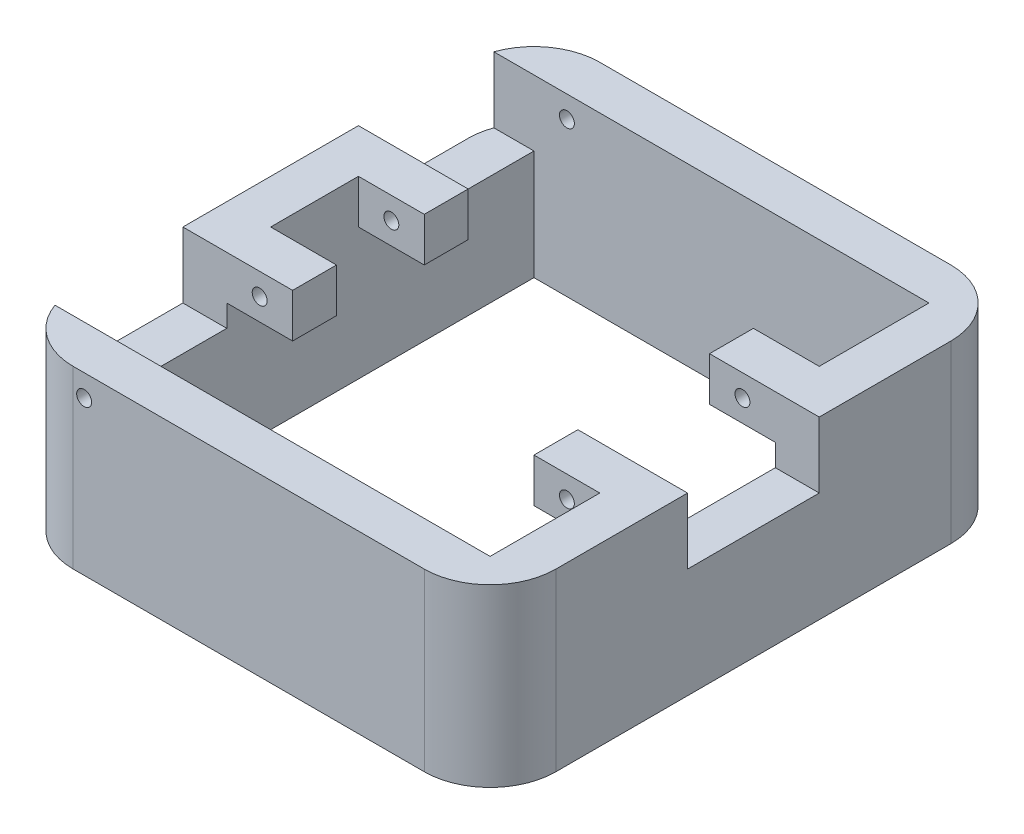
SolidWorks part; units mm, degrees
ref_plane "Front Plane" through (0, 0, 0) normal (0, 0, 1) x (1, 0, 0)
ref_plane "Top Plane" through (0, 0, 0) normal (0, 1, 0) x (1, 0, 0)
ref_plane "Right Plane" through (0, 0, 0) normal (1, 0, 0) x (0, 0, -1)
sketch "Sketch1" plane through (0, 0, 0) normal (0, 1, 0) x (1, 0, 0)
  line L1 (-45.2841, 33.3096) -> (34.7159, 33.3096)
  line L2 (-60.2841, 18.3096) -> (-60.2841, -71.6904)
  line L3 (-45.2841, -86.6904) -> (34.7159, -86.6904)
  line L4 (49.7159, 18.3096) -> (49.7159, -71.6904)
  line L5 (-50.2841, 23.3096) -> (39.7159, 23.3096)
  line L6 (-50.2841, 23.3096) -> (-50.2841, -76.6904)
  line L7 (-50.2841, -76.6904) -> (39.7159, -76.6904)
  line L8 (39.7159, 23.3096) -> (39.7159, -76.6904)
  arc A0 (-45.2841, 33.3096) -> (-60.2841, 18.3096) centre (-45.2841, 18.3096) ccw
  arc A1 (-60.2841, -71.6904) -> (-45.2841, -86.6904) centre (-45.2841, -71.6904) ccw
  arc A2 (34.7159, -86.6904) -> (49.7159, -71.6904) centre (34.7159, -71.6904) ccw
  arc A3 (49.7159, 18.3096) -> (34.7159, 33.3096) centre (34.7159, 18.3096) ccw
  dimension "D3" = 15
  dimension "D4" = 15
  dimension "D5" = 15
  dimension "D1" = 120
  dimension "D2" = 110
  dimension "D6" = 100
  dimension "D7" = 90
  dimension "D8" = 10
  dimension "D9" = 10
extrude "Boss-Extrude1" add sketch "Sketch1" along normal blind 40
sketch "Sketch3" plane through (0, 40, 0) normal (0, 1, 0) x (1, 0, 0)
  line L0 (-60.2841, -6.6904) -> (-35.2841, -6.6904)
  line L1 (-60.2841, 18.3096) -> (-60.2841, -71.6904) construction
  line L2 (-35.2841, -6.6904) -> (-35.2841, -46.6904)
  line L3 (-35.2841, -46.6904) -> (-60.2841, -46.6904)
  line L4 (-60.2841, -46.6904) -> (-60.2841, -6.6904)
  line L5 (39.7159, 23.3096) -> (-50.2841, 23.3096) construction
  line L6 (-50.2841, 23.3096) -> (-50.2841, -76.6904) construction
  dimension "D1" = 40
  dimension "D2" = 30
  dimension "D3" = 15
extrude "Boss-Extrude3" add sketch "Sketch3" against normal blind 10
sketch "Sketch5" plane through (0, 40, 0) normal (0, 1, 0) x (1, 0, 0)
  line L0 (-35.2841, -46.6904) -> (-35.2841, -6.6904) construction
  line L1 (-35.2841, -36.6904) -> (-50.2841, -36.6904)
  line L2 (-35.2841, -36.6904) -> (-35.2841, -16.6904)
  line L3 (-35.2841, -16.6904) -> (-50.2841, -16.6904)
  line L4 (-50.2841, -36.6904) -> (-50.2841, -16.6904)
  line L5 (-60.2841, 18.3096) -> (-60.2841, -71.6904) construction
  line L6 (-50.2841, -46.6904) -> (-35.2841, -46.6904) construction
  line L7 (-35.2841, -6.6904) -> (-50.2841, -6.6904) construction
  dimension "D1" = 10
  dimension "D2" = 10
  dimension "D3" = 10
extrude "Cut-Extrude1" cut sketch "Sketch5" against normal blind 10
sketch "Sketch6" plane through (0, 40, 0) normal (0, 1, 0) x (1, 0, 0)
  line L0 (49.7159, -71.6904) -> (49.7159, 18.3096) construction
  line L1 (49.7159, -51.6904) -> (24.7159, -51.6904)
  line L2 (49.7159, -51.6904) -> (49.7159, -41.6904)
  line L3 (49.7159, -41.6904) -> (24.7159, -41.6904)
  line L4 (24.7159, -51.6904) -> (24.7159, -41.6904)
  line L5 (-50.2841, -76.6904) -> (39.7159, -76.6904) construction
  line L6 (39.7159, -76.6904) -> (39.7159, 23.3096) construction
  line L7 (39.7159, 23.3096) -> (-50.2841, 23.3096) construction
  line L8 (49.7159, -1.6904) -> (24.7159, -1.6904)
  line L9 (49.7159, -1.6904) -> (49.7159, -11.6904)
  line L10 (49.7159, -11.6904) -> (24.7159, -11.6904)
  line L11 (24.7159, -1.6904) -> (24.7159, -11.6904)
  dimension "D1" = 10
  dimension "D2" = 25
  dimension "D3" = 15
  dimension "D4" = 10
  dimension "D5" = 25
extrude "Boss-Extrude4" add sketch "Sketch6" against normal blind 10
sketch "Sketch7" plane through (0, 40, 0) normal (0, 1, 0) x (1, 0, 0)
  line L0 (-60.2841, 18.3096) -> (-60.2841, -71.6904) construction
  line L1 (-50.2841, 23.3096) -> (-60.2841, 23.3096)
  line L2 (-50.2841, 23.3096) -> (-50.2841, -6.6904)
  line L3 (-50.2841, -6.6904) -> (-60.2841, -6.6904)
  line L4 (-60.2841, 23.3096) -> (-60.2841, -6.6904)
  line L5 (-35.2841, -6.6904) -> (-50.2841, -6.6904) construction
  line L6 (-50.2841, -46.6904) -> (-35.2841, -46.6904) construction
  line L7 (-50.2841, -76.6904) -> (-60.2841, -76.6904)
  line L8 (-50.2841, -76.6904) -> (-50.2841, -46.6904)
  line L9 (-50.2841, -46.6904) -> (-60.2841, -46.6904)
  line L10 (-60.2841, -76.6904) -> (-60.2841, -46.6904)
  line L11 (49.7159, -71.6904) -> (49.7159, 18.3096) construction
  line L12 (39.7159, -11.6904) -> (49.7159, -11.6904)
  line L13 (39.7159, -11.6904) -> (39.7159, -41.6904)
  line L14 (39.7159, -41.6904) -> (49.7159, -41.6904)
  line L15 (49.7159, -11.6904) -> (49.7159, -41.6904)
  line L16 (39.7159, -41.6904) -> (24.7159, -41.6904) construction
  dimension "D1" = 0
  dimension "D2" = 0
  dimension "D3" = 0
extrude "Cut-Extrude2" cut sketch "Sketch7" against normal blind 15
sketch "Sketch8" plane through (0, 0, 46.6904) normal (0, 0, 1) x (1, 0, 0)
  line L0 (-35.2841, 30) -> (-35.2841, 40) construction
  line L1 (-60.2841, 40) -> (-35.2841, 40) construction
  circle A0 centre (-42.7841, 35) radius 1.7
  dimension "D1" = 7.5
  dimension "D2" = 5
extrude "Cut-Extrude3" cut sketch "Sketch8" against normal through all both and the other way through all
sketch "Sketch9" plane through (0, 0, 51.6904) normal (0, 0, 1) x (1, 0, 0)
  line L0 (24.7159, 30) -> (24.7159, 40) construction
  line L1 (24.7159, 40) -> (39.7159, 40) construction
  circle A0 centre (32.2159, 35) radius 1.7
  dimension "D1" = 7.5
  dimension "D2" = 5
extrude "Cut-Extrude4" cut sketch "Sketch9" against normal blind 57
